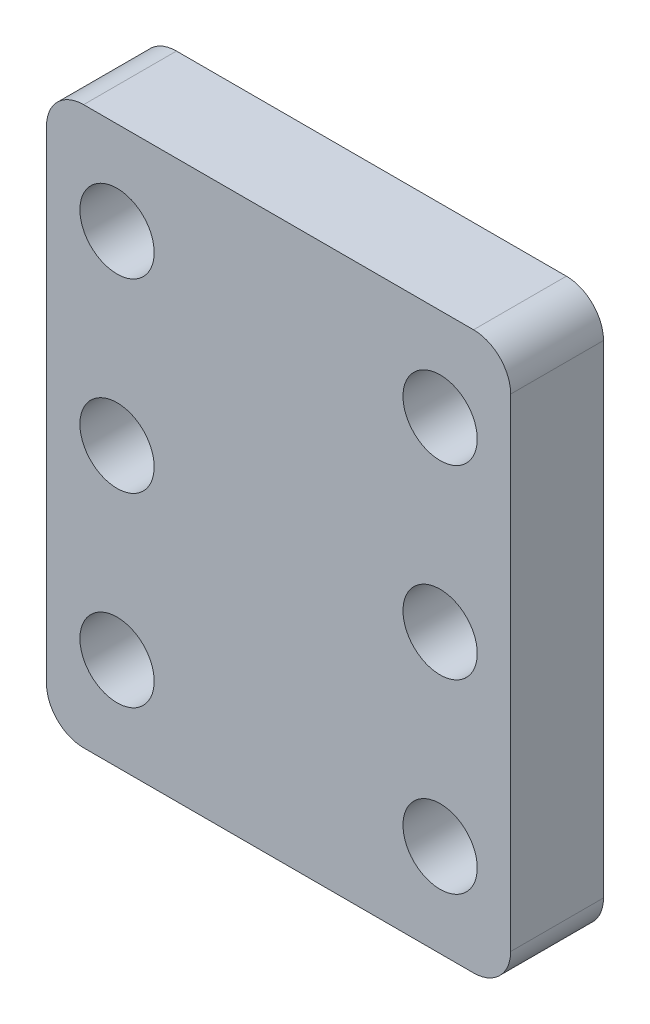
SolidWorks part; units mm, degrees
ref_plane "Front Plane" through (0, 0, 0) normal (0, 0, 1) x (1, 0, 0)
ref_plane "Top Plane" through (0, 0, 0) normal (0, 1, 0) x (1, 0, 0)
ref_plane "Right Plane" through (0, 0, 0) normal (1, 0, 0) x (0, 0, -1)
sketch "Sketch1" plane through (0, 0, 0) normal (0, 0, 1) x (1, 0, 0)
  line L0 (-41.4867, 36.7242) -> (-41.4867, -1.3758)
  line L1 (-41.4867, -1.3758) -> (-9.7367, -1.3758)
  line L2 (-9.7367, -1.3758) -> (-9.7367, 36.7242)
  line L3 (-9.7367, 36.7242) -> (-41.4867, 36.7242)
  dimension "D1" = 38.1
  dimension "D2" = 31.75
extrude "Boss-Extrude1" add sketch "Sketch1" along normal blind 6.35
fillet "Fillet1" radius 2.54 4 edges at (-9.7367, 36.7242, 3.175) (-9.7367, -1.3758, 3.175) (-41.4867, -1.3758, 3.175) (-41.4867, 36.7242, 3.175)
sketch "Sketch3" plane through (0, 0, 6.35) normal (0, 0, 1) x (1, 0, 0)
  line L0 (-38.9467, 36.7242) -> (-41.4867, 34.1842) construction
sketch "Sketch4" plane through (0, 0, 6.35) normal (0, 0, 1) x (1, 0, 0)
  line L0 (-9.7367, 1.1642) -> (-9.7367, 34.1842) construction
  line L1 (-12.2767, 36.7242) -> (-38.9467, 36.7242) construction
  line L2 (-25.6117, 36.7242) -> (-25.6117, -1.3758) construction
  line L3 (-38.9467, -1.3758) -> (-12.2767, -1.3758) construction
  circle A0 centre (-14.5627, 30.3742) radius 2.54
  circle A1 centre (-14.5627, 17.6742) radius 2.54
  circle A2 centre (-14.5627, 4.9742) radius 2.54
  circle A3 centre (-36.6607, 4.9742) radius 2.54
  circle A4 centre (-36.6607, 17.6742) radius 2.54
  circle A5 centre (-36.6607, 30.3742) radius 2.54
  dimension "D1" = 4.826
  dimension "D2" = 6.35
  dimension "D3" = 3
extrude "Cut-Extrude1" cut sketch "Sketch4" against normal blind 6.35
